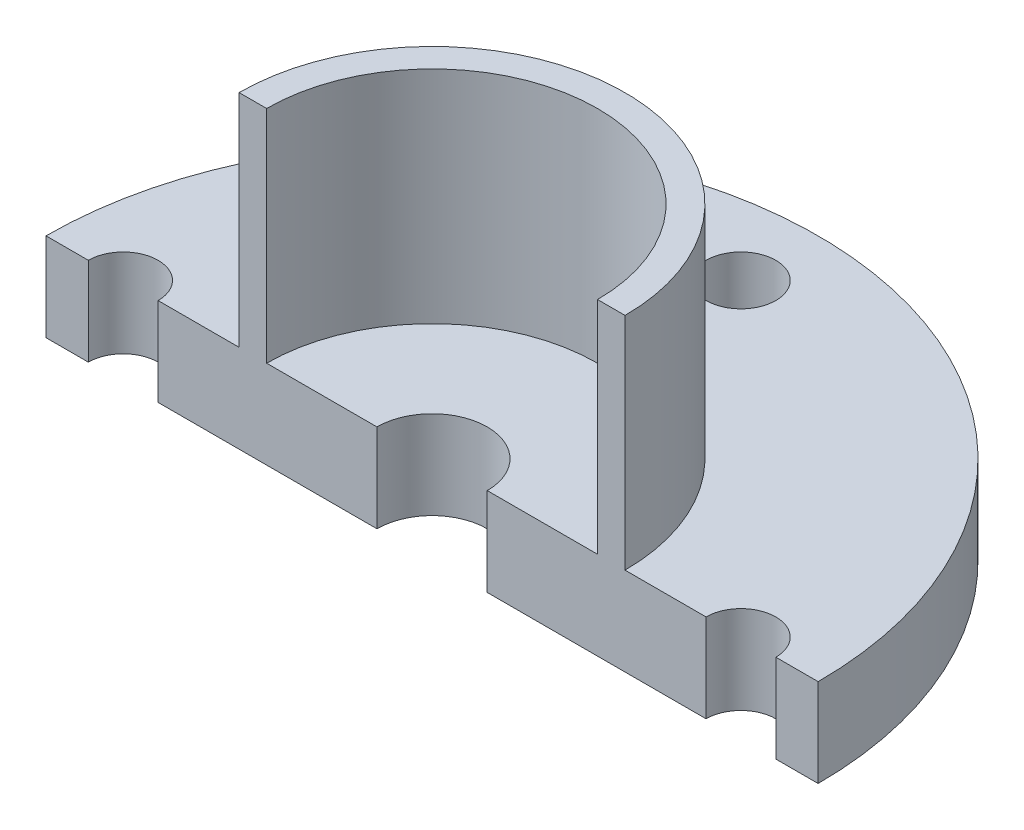
SolidWorks part; units mm, degrees
ref_plane "Plan1" through (0, 0, 0) normal (0, 0, 1) x (1, 0, 0)
ref_plane "Plan2" through (0, 0, 0) normal (0, 1, 0) x (1, 0, 0)
ref_plane "Plan3" through (0, 0, 0) normal (1, 0, 0) x (0, 0, -1)
sketch "Esquisse2" plane through (0, 0, 0) normal (0, 1, 0) x (1, 0, 0)
  circle A0 centre (0, 0) radius 35 construction
  circle A1 centre (0, 0) radius 35
  circle A2 centre (0, 0) radius 5 construction
  circle A3 centre (-28, 0) radius 3.1623 construction
  circle A4 centre (0, 28) radius 3.1623 construction
  circle A5 centre (0, -28) radius 3.1623 construction
  circle A6 centre (28, 0) radius 3.1623 construction
  circle A7 centre (0, 0) radius 5
  circle A8 centre (-28, 0) radius 3.1623
  circle A9 centre (0, 28) radius 3.1623
  circle A10 centre (0, -28) radius 3.1623
  circle A11 centre (28, 0) radius 3.1623
extrude "Base-Extrusion" add sketch "Esquisse2" along normal blind 8
sketch "Esquisse3" plane through (0, 8, 0) normal (0, 1, 0) x (-1, 0, 0)
  circle A0 centre (0, 0) radius 15 construction
  circle A1 centre (0, 0) radius 15
  circle A2 centre (0, 0) radius 17.4929
extrude "Boss.-Extru.1" add sketch "Esquisse3" along normal blind 20
sketch "Esquisse4" plane through (0, 0, 0) normal (0, 1, 0) x (1, 0, 0)
  line L1 (-37, 0) -> (35, 0)
  line L2 (-37, 0) -> (-37, -33)
  line L3 (-37, -33) -> (35, -33)
  line L4 (35, 0) -> (35, -33)
extrude "Enlèv. mat.-Extru.2" cut sketch "Esquisse4" along normal through all
